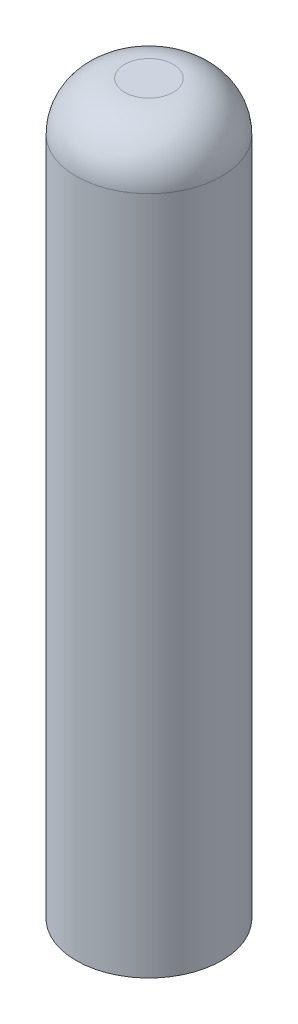
SolidWorks part; units mm, degrees
ref_plane "Front Plane" through (0, 0, 0) normal (0, 0, 1) x (1, 0, 0)
ref_plane "Top Plane" through (0, 0, 0) normal (0, 1, 0) x (1, 0, 0)
ref_plane "Right Plane" through (0, 0, 0) normal (1, 0, 0) x (0, 0, -1)
sketch "Sketch1" plane through (0, 0, 0) normal (0, 1, 0) x (1, 0, 0)
  circle A0 centre (0, 0) radius 1.5
  dimension "D1" = 3
extrude "Boss-Extrude1" add sketch "Sketch1" along normal blind 15
fillet "Fillet1" radius 1 1 edges at (0, 15, 1.5)
